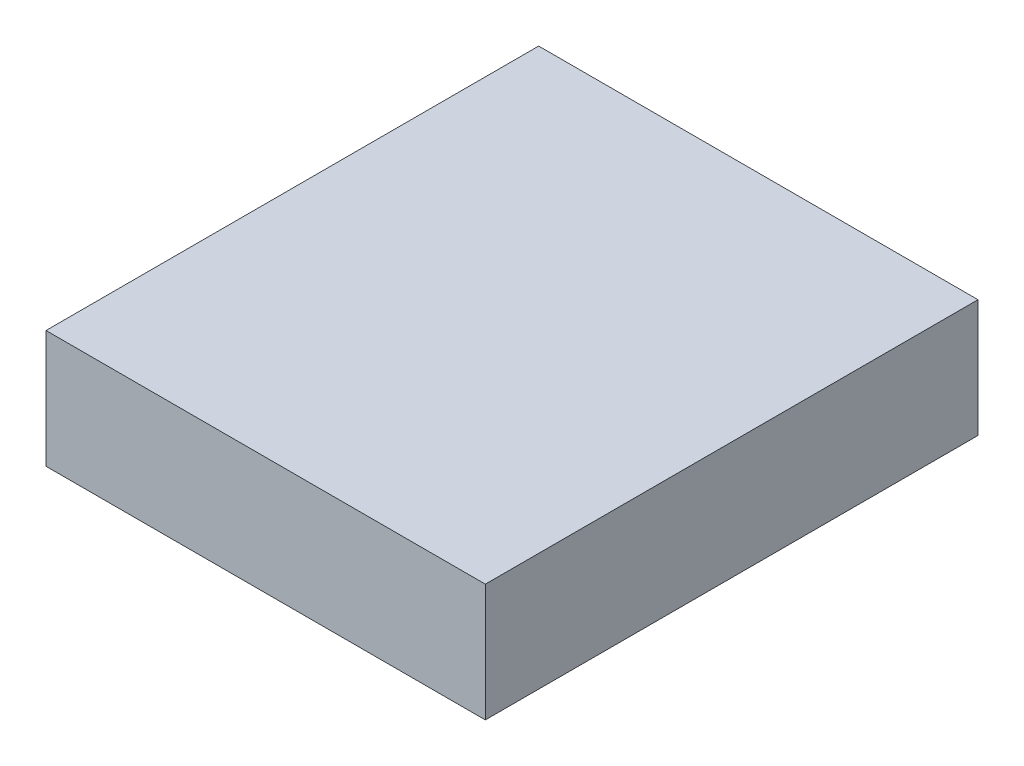
SolidWorks part; units mm, degrees
ref_plane "Спереди" through (0, 0, 0) normal (0, 0, 1) x (1, 0, 0)
ref_plane "Сверху" through (0, 0, 0) normal (0, 1, 0) x (1, 0, 0)
ref_plane "Справа" through (0, 0, 0) normal (1, 0, 0) x (0, 0, -1)
sketch "Эскиз1" plane through (0, 0, 0) normal (0, 1, 0) x (1, 0, 0)
  line L1 (0, 0) -> (-37.3546, 0)
  line L2 (0, 0) -> (0, 41.8897)
  line L3 (0, 41.8897) -> (-37.3546, 41.8897)
  line L4 (-37.3546, 0) -> (-37.3546, 41.8897)
extrude "Бобышка-Вытянуть1" add sketch "Эскиз1" along normal blind 10 contours L4 L3 L2 L1
